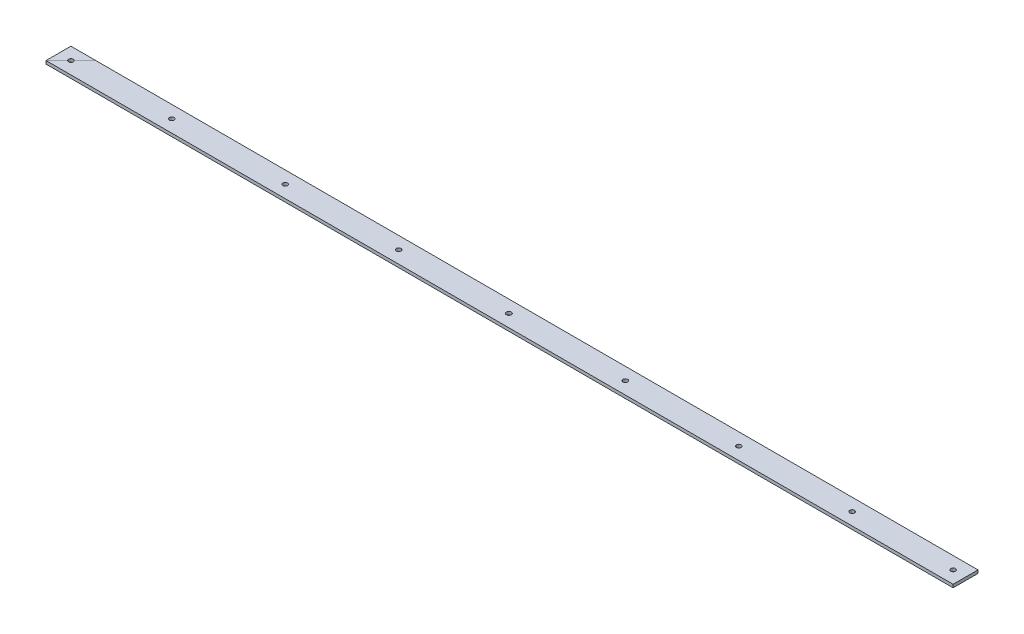
SolidWorks part; units mm, degrees
ref_plane "Alzado" through (0, 0, 0) normal (0, 0, 1) x (1, 0, 0)
ref_plane "Planta" through (0, 0, 0) normal (0, 1, 0) x (1, 0, 0)
ref_plane "Vista lateral" through (0, 0, 0) normal (1, 0, 0) x (0, 0, -1)
sketch "Croquis2" plane through (0, 0, 0) normal (0, 1, 0) x (1, 0, 0)
  line L1 (-25.4, 3.155) -> (25.4, 3.155)
  line L2 (-25.4, 3.155) -> (-25.4, -3.155)
  line L3 (-25.4, -3.155) -> (25.4, -3.155)
  line L4 (25.4, 3.155) -> (25.4, -3.155)
  line L5 (-25.4, 3.155) -> (25.4, -3.155) construction
  line L6 (-25.4, -3.155) -> (25.4, 3.155) construction
  line L7 (238.1, 3.155) -> (288.9, 3.155)
  line L8 (238.1, 3.155) -> (238.1, -3.155)
  line L9 (238.1, -3.155) -> (288.9, -3.155)
  line L10 (288.9, 3.155) -> (288.9, -3.155)
  line L11 (238.1, 3.155) -> (288.9, -3.155) construction
  line L12 (238.1, -3.155) -> (288.9, 3.155) construction
  point P0 (0, 0)
  point P6 (263.5, 0)
  dimension "D1" = 50.8
  dimension "D2" = 6.31
  dimension "D3" = 263.5
  dimension "D4" = 50.8
  dimension "D5" = 6.31
sketch3d "Croquis3D1"
  line L0 (0, 0, 0) -> (0, -567.24, 0)
  line L1 (0, -567.24, 0) -> (0, -567.24, 316.2)
  line L2 (0, -567.24, 316.2) -> (1793.15, -567.24, 316.2)
  line L3 (1793.15, -567.24, 316.2) -> (1793.15, -567.24, 578)
  line L4 (-25.4, 0, 0) -> (-25.4, -383.9185, 0) construction
  line L5 (-25.4, 0, -3.155) -> (-25.4, 0, 3.155) construction
  line L6 (-25.4, -383.9185, 0) -> (-25.4, -383.9185, 653.2834) construction
  line L7 (1793.15, -567.24, 578) -> (1793.15, -435.4728, 578)
  line L8 (1793.15, -435.4728, 578) -> (1793.15, -435.4728, 1432.0029)
  dimension "D1" = 567.24
  dimension "D2" = 316.2
  dimension "D3" = 1793.15
  dimension "D4" = 261.8
  dimension "D5" = 131.7672
  dimension "D6" = 854.0029
sweep "Barrer1" add profiles "Croquis2" path "Croquis3D1"
sketch "Croquis3" plane through (0, 0, -3.155) normal (0, 0, -1) x (-1, 0, 0)
  line L0 (-288.9, 0) -> (-288.9, -6.31)
  line L1 (-288.9, 0) -> (-288.9, -570.395) construction
  line L2 (-288.9, -6.31) -> (-238.1, -6.31)
  line L3 (-238.1, 0) -> (-238.1, -570.395) construction
  line L4 (-238.1, -6.31) -> (-238.1, 0)
  line L5 (-238.1, 0) -> (-288.9, 0)
  line L7 (-25.4, 0) -> (-25.4, -6.31)
  line L8 (-25.4, 0) -> (-25.4, -570.395) construction
  line L9 (-25.4, -6.31) -> (25.4, -6.31)
  line L10 (25.4, 0) -> (25.4, -570.395) construction
  line L11 (25.4, -6.31) -> (25.4, 0)
  line L12 (-25.4, 0) -> (25.4, 0) construction
  line L13 (25.4, 0) -> (-25.4, 0)
  dimension "D1" = 6.31
  dimension "D2" = 6.31
sketch3d "Croquis3D2"
  line L0 (25.4, -3.155, -3.155) -> (-0.201, -3.155, -3.155) construction
  line L1 (25.4, 0, -3.155) -> (25.4, -6.31, -3.155) construction
  line L2 (-0.201, -3.155, -3.155) -> (-0.201, -5.2746, -3.155) construction
  line L3 (-0.201, -3.155, -3.155) -> (-0.201, -3.155, -207.155)
  line L4 (-0.201, -3.155, -207.155) -> (-0.201, -53.155, -207.155)
  dimension "D1" = 204
  dimension "D2" = 50
sweep "Barrer4" add profiles "Croquis3" path "Croquis3D2"
sketch "Croquis4" plane through (0, 0, -210.31) normal (0, 0, -1) x (-1, 0, 0)
  line L0 (-238.1, 0) -> (-238.1, -53.155)
  line L1 (-238.1, -53.155) -> (-178.1, -53.155)
  line L2 (-178.1, -53.155) -> (-178.1, 0)
  line L3 (-178.1, 0) -> (-238.1, 0)
  dimension "D1" = 60
extrude "Saliente-Extruir1" add sketch "Croquis4" against normal blind 6.31
sketch "Croquis5" plane through (0, 0, -204) normal (0, 0, 1) x (1, 0, 0)
  line L0 (238.1, -6.31) -> (178.1, -6.31)
  line L1 (178.1, -53.155) -> (178.1, 0) construction
  line L2 (178.1, -6.31) -> (178.1, 0)
  line L3 (178.1, 0) -> (238.1, 0)
  line L4 (238.1, 0) -> (238.1, -6.31)
extrude "Cortar-Extruir1" cut sketch "Croquis5" against normal blind 6.31
sketch "Croquis6" plane through (0, -432.3178, 0) normal (0, 1, 0) x (1, 0, 0)
  circle A0 centre (1285.7, -1260.295) radius 4.75
  circle A1 centre (1495.7, -1260.295) radius 4.75
sketch "Croquis7" plane through (0, 0, 3.155) normal (0, 0, 1) x (1, 0, 0)
  line L0 (288.9, -564.085) -> (238.1, -564.085)
  line L1 (238.1, -564.085) -> (238.1, -68.8755)
  line L2 (238.1, 0) -> (238.1, -564.085) construction
  line L3 (238.1, -68.8755) -> (170.6111, -68.8755)
  line L4 (170.6111, -68.8755) -> (170.6111, 0)
  line L5 (170.6111, 0) -> (288.9, 0)
  line L6 (288.9, 0) -> (288.9, -564.085)
extrude "Cortar-Extruir2" cut sketch "Croquis7" against normal blind 502
sketch "Croquis8" plane through (0, 0, 3.155) normal (0, 0, 1) x (1, 0, 0)
  line L0 (25.4, -564.085) -> (-25.4, -564.085)
  line L1 (-25.4, -564.085) -> (-25.4, 0)
  line L2 (-25.4, 0) -> (25.4, 0)
  line L3 (25.4, 0) -> (25.4, -564.085)
extrude "Cortar-Extruir3" cut sketch "Croquis8" against normal blind 502
sketch "Croquis9" plane through (0, -432.3178, 0) normal (0, 1, 0) x (1, 0, 0)
  line L0 (1767.75, -341.6) -> (2082.05, -341.6)
  line L1 (2082.05, -27.3) -> (2082.05, -574.845) construction
  line L2 (2082.05, -341.6) -> (2082.05, -1432.0029)
  line L3 (2082.05, -1432.0029) -> (1767.75, -1432.0029)
  line L4 (1767.75, -341.6) -> (1767.75, -1432.0029)
extrude "Cortar-Extruir4" cut sketch "Croquis9" against normal blind 502
sketch "Croquis10" plane through (0, 0, -3.155) normal (0, 0, -1) x (-1, 0, 0)
  line L0 (-25.4, -564.085) -> (25.4, -564.085)
  line L1 (25.4, -564.085) -> (25.4, -570.395)
  line L2 (25.4, -570.395) -> (-25.4, -570.395)
  line L3 (-25.4, -570.395) -> (-25.4, -564.085)
extrude "Cortar-Extruir5" cut sketch "Croquis10" against normal blind 95
sketch "Croquis11" plane through (0, -564.085, 0) normal (0, 1, 0) x (1, 0, 0)
  line L0 (288.9, -27.3) -> (238.1, -27.3)
  line L1 (238.1, -3.155) -> (238.1, -78.1) construction
  line L2 (238.1, -78.1) -> (288.9, -78.1)
  line L3 (238.1, -78.1) -> (2031.25, -78.1) construction
  line L4 (288.9, -78.1) -> (288.9, -27.3)
  line L5 (288.9, -27.3) -> (288.9, 3.155)
  line L6 (288.9, 3.155) -> (238.1, 3.155)
  line L7 (238.1, 3.155) -> (238.1, -27.3)
  line M1 (288.9, -27.3) -> (288.9, -3.155)
  line M2 (288.9, -3.155) -> (288.9, 3.155)
  line M3 (288.9, 3.155) -> (238.1, 3.155)
  line M4 (238.1, 3.155) -> (238.1, -3.155)
  line M5 (238.1, -3.155) -> (238.1, -78.1)
  line M6 (238.1, -78.1) -> (288.9, -27.3)
extrude "Cortar-Extruir6" cut sketch "Croquis11" against normal blind 95 contours L2 L4 M6 | L0 M6 M5 | L0 M1 M2 M3 M4 M5
sketch "Croquis13" plane through (0, -564.085, 0) normal (0, 1, 0) x (1, 0, 0)
  line L0 (-25.4, -91.845) -> (-25.4, -341.6)
  line L1 (-25.4, -341.6) -> (94.6, -341.6)
  line L2 (-25.4, -341.6) -> (1767.75, -341.6) construction
  line L3 (94.6, -341.6) -> (94.6, -91.845)
  line L4 (94.6, -91.845) -> (-25.4, -91.845)
  dimension "D1" = 120
extrude "Cortar-Extruir7" cut sketch "Croquis13" against normal blind 95
sketch "Croquis16" plane through (0, -564.085, 0) normal (0, 1, 0) x (1, 0, 0)
  line L2 (288.9, -27.3) -> (163.9, -27.3)
  line L3 (163.9, -27.3) -> (163.9, -78.1)
  line L4 (163.9, -78.1) -> (288.9, -78.1)
  line L5 (288.9, -27.3) -> (288.9, -78.1)
  dimension "D1" = 125
extrude "Saliente-Extruir4" add sketch "Croquis16" against normal blind 6.31
sketch "Croquis17" plane through (94.6, 0, 0) normal (-1, 0, 0) x (0, 0, 1)
  line L0 (290.8, -564.085) -> (290.8, -570.395)
  line L1 (290.8, -570.395) -> (341.6, -570.395)
  line L2 (341.6, -570.395) -> (341.6, -564.085)
  line L3 (341.6, -564.085) -> (290.8, -564.085)
  line L4 (316.2, -564.085) -> (316.2, -570.395) construction
  line L5 (316.2, -570.395) -> (316.2, -567.24) construction
  line L6 (316.2, -567.24) -> (341.6, -567.24) construction
sketch3d "Croquis3D3"
  line L0 (94.6, -567.24, 316.2) -> (46.55, -567.24, 316.2)
  line L1 (46.55, -567.24, 316.2) -> (46.55, -567.24, 105.72)
  dimension "D1" = 48.05
  dimension "D2" = 210.48
sweep "Barrer5" add profiles "Croquis17" path "Croquis3D3"
sketch "Croquis18" plane through (21.15, 0, 0) normal (-1, 0, 0) x (0, 0, 1)
  line L0 (98.7872, -564.085) -> (98.7872, -435.523)
  line L1 (341.6, -564.085) -> (105.72, -564.085) construction
  line L2 (98.7872, -435.523) -> (64.97, -367.6227)
  line L3 (64.97, -367.6227) -> (59.3217, -370.4358)
  line L4 (59.3217, -370.4358) -> (91.8975, -435.8435)
  line L5 (91.8975, -435.8435) -> (91.8429, -564.085)
  line L6 (91.8429, -564.085) -> (98.7872, -564.085)
  dimension "D1" = 6.31
extrude "Saliente-Extruir5" add sketch "Croquis18" against normal blind 50.8
sketch "Croquis20" plane through (163.9, 0, 0) normal (-1, 0, 0) x (0, 0, 1)
  line L0 (78.1, -564.085) -> (78.1, -439.8845)
  line L1 (78.1, -439.8845) -> (59.9661, -387.9255)
  line L2 (59.9661, -387.9255) -> (54.0085, -390.0047)
  line L3 (54.0085, -390.0047) -> (71.79, -440.954)
  line L4 (71.79, -440.954) -> (71.79, -564.085)
  line L5 (27.3, -564.085) -> (78.1, -564.085) construction
  line L6 (71.79, -564.085) -> (78.1, -564.085)
  dimension "D1" = 6.31
  dimension "D2" = 6.31
extrude "Saliente-Extruir6" add sketch "Croquis20" against normal blind 50.8
sketch "Croquis21" plane through (0, -564.085, 0) normal (0, 1, 0) x (1, 0, 0)
  line L0 (1818.55, -290.8) -> (1808.55, -290.8)
  line L1 (71.95, -290.8) -> (1818.55, -290.8) construction
  line L2 (1808.55, -290.8) -> (1808.55, -341.6)
  line L3 (1767.75, -341.6) -> (1818.55, -341.6) construction
  line L4 (1808.55, -341.6) -> (1818.55, -341.6)
  line L5 (1818.55, -341.6) -> (1818.55, -290.8)
  dimension "D1" = 10
extrude "Cortar-Extruir9" cut sketch "Croquis21" against normal blind 53
sketch "Croquis22" plane through (0, -564.085, 0) normal (0, 1, 0) x (1, 0, 0)
  line L1 (71.95, -290.8) -> (71.95, -341.6)
  line L2 (21.15, -341.6) -> (1767.75, -341.6) construction
  line L3 (71.95, -341.6) -> (72.05, -341.6)
  line L4 (72.05, -341.6) -> (72.05, -290.8)
  line L5 (71.95, -290.8) -> (1808.55, -290.8) construction
  line L6 (72.05, -290.8) -> (71.95, -290.8)
  dimension "D1" = 0.1
extrude "Cortar-Extruir10" cut sketch "Croquis22" against normal blind 10
sketch "Croquis23" plane through (0, -570.395, 0) normal (0, -1, 0) x (1, 0, 0)
  line L0 (2031.25, 341.6) -> (2031.25, 78.1)
  line L1 (2031.25, 78.1) -> (163.9, 78.1)
  line L2 (163.9, 78.1) -> (163.9, 0)
  line L3 (163.9, 0) -> (2111.3004, 0)
  line L4 (2111.3004, 0) -> (2111.3004, 341.6)
  line L5 (2111.3004, 341.6) -> (2031.25, 341.6)
extrude "Cortar-Extruir11" cut sketch "Croquis23" against normal blind 237
sketch "Croquis24" plane through (0, 0, 98.7872) normal (0, 0, 1) x (1, 0, 0)
  line L0 (21.15, -564.085) -> (71.95, -564.085)
  line L1 (71.95, -564.085) -> (71.95, -359.0988)
  line L2 (71.95, -359.0988) -> (21.15, -359.0988)
  line L3 (21.15, -359.0988) -> (21.15, -564.085)
extrude "Cortar-Extruir12" cut sketch "Croquis24" against normal blind 237
sketch "Croquis25" plane through (0, 0, 105.72) normal (0, 0, -1) x (-1, 0, 0)
  line L0 (-71.95, -570.395) -> (-71.95, -564.085)
  line L1 (-71.95, -564.085) -> (-21.15, -564.085)
  line L2 (-21.15, -564.085) -> (-21.15, -570.395)
  line L3 (-21.15, -570.395) -> (-71.95, -570.395)
extrude "Saliente-Extruir7" add sketch "Croquis25" along normal blind 1.1
sketch "Croquis26" plane through (1808.55, 0, 0) normal (1, 0, 0) x (0, 0, -1)
  line L0 (-341.6, -564.085) -> (-341.6, -570.395)
  line L1 (-341.6, -570.395) -> (-290.8, -570.395)
  line L2 (-290.8, -570.395) -> (-290.8, -564.085)
  line L3 (-290.8, -564.085) -> (-341.6, -564.085)
extrude "Saliente-Extruir8" add sketch "Croquis26" along normal blind 12.7
sketch "Croquis27" plane through (0, -564.085, 0) normal (0, 1, 0) x (1, 0, 0)
  line L0 (940.2, -316.2) -> (948.9952, -313.3353) construction
  circle A0 centre (940.2, -316.2) radius 5
  dimension "D1" = 10
extrude "Cortar-Extruir13" cut sketch "Croquis27" against normal blind 10
sketch "Croquis28" plane through (0, -564.085, 0) normal (0, 1, 0) x (1, 0, 0)
  line L0 (71.95, -341.6) -> (72.05, -341.6)
  line L1 (72.05, -341.6) -> (72.05, -290.8)
  line L2 (72.05, -290.8) -> (71.95, -290.8)
  line L3 (71.95, -290.8) -> (71.95, -341.6)
extrude "Saliente-Extruir9" add sketch "Croquis28" against normal up to surface (6.31 mm away)
sketch "Croquis29" plane through (0, -564.085, 0) normal (0, 1, 0) x (1, 0, 0)
  line L0 (71.95, -290.8) -> (21.15, -290.8)
  line L1 (21.15, -341.6) -> (21.15, -104.62) construction
  line L2 (21.15, -290.8) -> (21.15, -290.7)
  line L3 (21.15, -290.7) -> (71.95, -290.7)
  line L4 (71.95, -290.8) -> (71.95, -104.62) construction
  line L5 (71.95, -290.7) -> (71.95, -290.8)
  dimension "D1" = 0.1
extrude "Cortar-Extruir14" cut sketch "Croquis29" against normal blind 50
sketch "Croquis30" plane through (1821.25, 0, 0) normal (1, 0, 0) x (0, 0, -1)
  line L0 (-341.6, -564.085) -> (-341.6, -570.395)
  line L1 (-341.6, -570.395) -> (-290.8, -570.395)
  line L2 (-290.8, -570.395) -> (-290.8, -564.085)
  line L3 (-290.8, -564.085) -> (-341.6, -564.085)
extrude "Saliente-Extruir10" add sketch "Croquis30" along normal blind 50.8
sketch "Croquis31" plane through (0, -564.085, 0) normal (0, 1, 0) x (1, 0, 0)
  line L0 (1872.05, -316.2) -> (1846.65, -316.2) construction
  line L1 (1872.05, -290.8) -> (1872.05, -341.6) construction
  line L2 (1846.65, -316.2) -> (1846.65, -290.8) construction
  line L3 (1872.05, -290.8) -> (71.95, -290.8) construction
  circle A0 centre (1846.65, -316.2) radius 4.7625
  dimension "D2" = 9.525
  dimension "D1" = 25.4
extrude "Cortar-Extruir15" cut sketch "Croquis31" against normal blind 10
sketch "Croquis32" plane through (0, -564.085, 0) normal (0, 1, 0) x (1, 0, 0)
  line L0 (21.15, -316.2) -> (71.95, -316.2) construction
  line L1 (21.15, -341.6) -> (21.15, -290.8) construction
  line L2 (71.95, -316.2) -> (46.55, -316.2) construction
  line L3 (46.55, -316.2) -> (46.55, -290.8) construction
  line L4 (21.15, -290.8) -> (71.95, -290.8) construction
  circle A0 centre (46.55, -316.2) radius 4.7625
  dimension "D1" = 9.525
extrude "Cortar-Extruir16" cut sketch "Croquis32" against normal blind 33
sketch "Croquis33" plane through (0, -570.395, 0) normal (0, -1, 0) x (-1, 0, 0)
  circle A0 centre (-33.85, -252.7) radius 4.7625
  circle A1 centre (-59.25, -278.1) radius 4.7625
extrude "Cortar-Extruir17" cut sketch "Croquis33" against normal blind 50
sketch "Croquis34" plane through (0, -564.085, 0) normal (0, 1, 0) x (1, 0, 0)
  line L0 (1872.05, -316.2) -> (21.15, -316.2) construction
  line L1 (1872.05, -290.8) -> (1872.05, -341.6) construction
  line L2 (21.15, -341.6) -> (21.15, -290.8) construction
  line L3 (21.15, -316.2) -> (946.6, -316.2) construction
  line L4 (946.6, -316.2) -> (483.875, -316.2) construction
  line L5 (483.875, -316.2) -> (21.15, -316.2) construction
  line L6 (21.15, -316.2) -> (252.5125, -316.2) construction
  line L7 (483.875, -316.2) -> (946.6, -316.2) construction
  line L8 (946.6, -316.2) -> (715.2375, -316.2) construction
  line L9 (946.6, -316.2) -> (1872.05, -316.2) construction
  line L10 (1872.05, -316.2) -> (1409.325, -316.2) construction
  line L11 (1872.05, -316.2) -> (1409.325, -316.2) construction
  line L12 (1409.325, -316.2) -> (1640.6875, -316.2) construction
  line L13 (1640.6875, -316.2) -> (1640.6875, -245.0018) construction
  line L14 (1409.325, -316.2) -> (946.6, -316.2) construction
  line L15 (946.6, -316.2) -> (1177.9625, -316.2) construction
  circle A0 centre (1640.6875, -316.2) radius 4.7625
  circle A1 centre (1409.325, -316.2) radius 4.7625
  circle A2 centre (1177.9625, -316.2) radius 4.7625
  circle A3 centre (715.2375, -316.2) radius 4.7625
  circle A4 centre (483.875, -316.2) radius 4.7625
  circle A5 centre (252.5125, -316.2) radius 4.7625
  dimension "D1" = 9.525
  dimension "D2" = 9.525
  dimension "D3" = 9.525
  dimension "D4" = 9.525
  dimension "D5" = 9.525
  dimension "D6" = 9.525
extrude "Cortar-Extruir18" cut sketch "Croquis34" against normal blind 82
sketch "Croquis35" plane through (0, -564.085, 0) normal (0, 1, 0) x (1, 0, 0)
  line L0 (21.15, -156.0272) -> (21.15, -160.8021) construction
  line L1 (21.15, -290.7) -> (21.15, -104.62) construction
  line L2 (21.15, -160.8021) -> (46.5521, -160.8021) construction
  line L3 (46.5521, -160.8021) -> (46.5521, -193.7414) construction
  circle A0 centre (46.5521, -160.8021) radius 5
  dimension "D1" = 10
extrude "Cortar-Extruir19" cut sketch "Croquis35" against normal blind 10
sketch "Croquis36" plane through (0, -564.085, 0) normal (0, 1, 0) x (1, 0, 0)
  line L0 (21.15, -290.7) -> (21.15, -104.62)
  line L1 (21.15, -104.62) -> (71.95, -104.62)
  line L2 (71.95, -104.62) -> (71.95, -290.7)
  line L3 (71.95, -290.7) -> (21.15, -290.7)
extrude "Cortar-Extruir20" cut sketch "Croquis36" against normal blind 10
